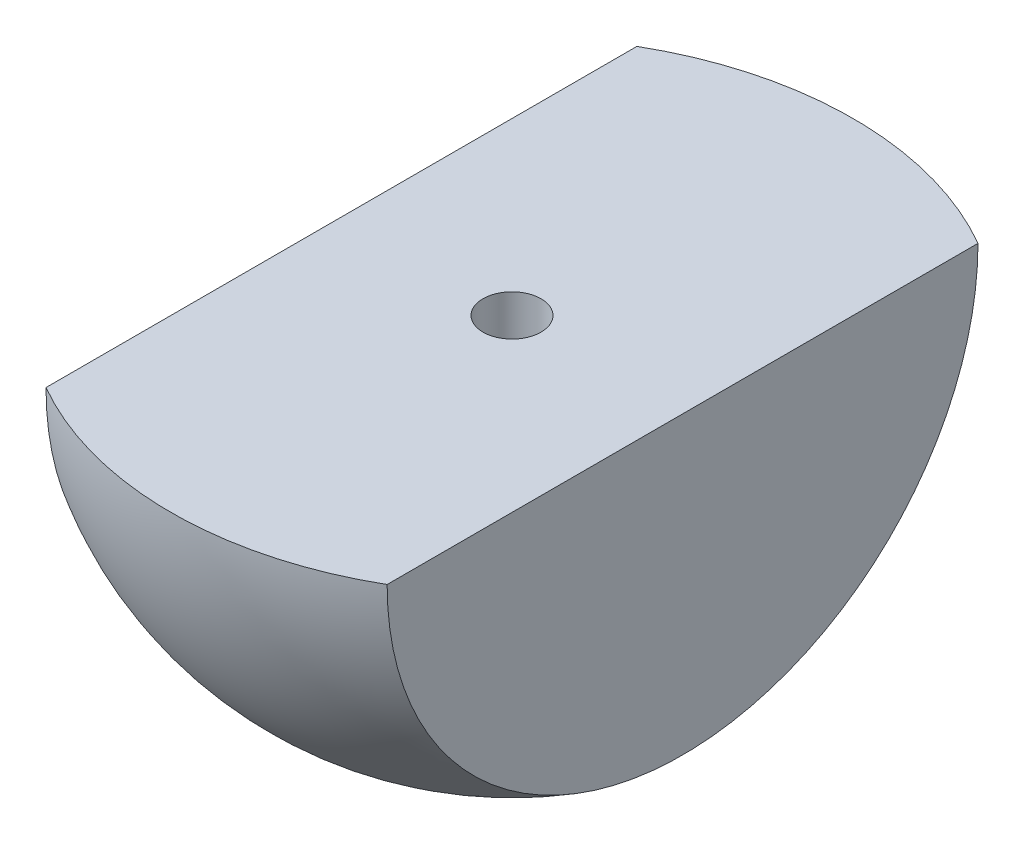
SolidWorks part; units mm, degrees
ref_plane "Front Plane" through (0, 0, 0) normal (0, 0, 1) x (1, 0, 0)
ref_plane "Top Plane" through (0, 0, 0) normal (0, 1, 0) x (1, 0, 0)
ref_plane "Right Plane" through (0, 0, 0) normal (1, 0, 0) x (0, 0, -1)
sketch "Sketch1" plane through (0, 0, 0) normal (0, 1, 0) x (1, 0, 0)
  line L0 (20, 0) -> (-20, 0)
  arc A0 (20, 0) -> (-20, 0) centre (0, 0) ccw
  dimension "D1" = 40
revolve "Revolve1" add sketch "Sketch1" angle 180 about L0
sketch "Sketch2" plane through (0, 0, 0) normal (0, 1, 0) x (1, 0, 0)
  line L0 (-10, 0) -> (10, 0) construction
  line L1 (-30, 22.5) -> (-10, 22.5)
  line L2 (-30, 22.5) -> (-30, -22.5)
  line L3 (-30, -22.5) -> (-10, -22.5)
  line L4 (-10, 22.5) -> (-10, -22.5)
  line L5 (10, 22.5) -> (30, 22.5)
  line L6 (10, 22.5) -> (10, -22.5)
  line L7 (10, -22.5) -> (30, -22.5)
  line L8 (30, 22.5) -> (30, -22.5)
  dimension "D1" = 20
  dimension "D2" = 45
  dimension "D3" = 20
extrude "Cut-Extrude1" cut sketch "Sketch2" against normal through all
hole_wizard "CBORE for M3 SHCS1" positions "3DSketch1" profile "Sketch3" counterbore size "M3" standard "ANSI Metric" end condition through all
sketch3d "3DSketch1"
  point P0 (0, -20, 0)
sketch "Sketch3" plane through (0, -20, 0) normal (1, 0, 0) x (0, 0, -1)
  line L0 (0, 0) -> (0, 20)
  line L1 (0, 20) -> (1.7, 20)
  line L3 (1.7, 20) -> (1.7, 4)
  line L4 (1.7, 4) -> (3.25, 4)
  line L5 (3.25, 4) -> (3.25, 0)
  line L7 (3.25, 0) -> (0, 0)
  line L11 (0, -6.35) -> (0, 107.95) construction
  dimension "Thru Hole Dia." = 3.4
  dimension "Thru Hole Depth" = 20
  dimension "C'Bore Dia." = 6.5
  dimension "C'Bore Depth" = 4
